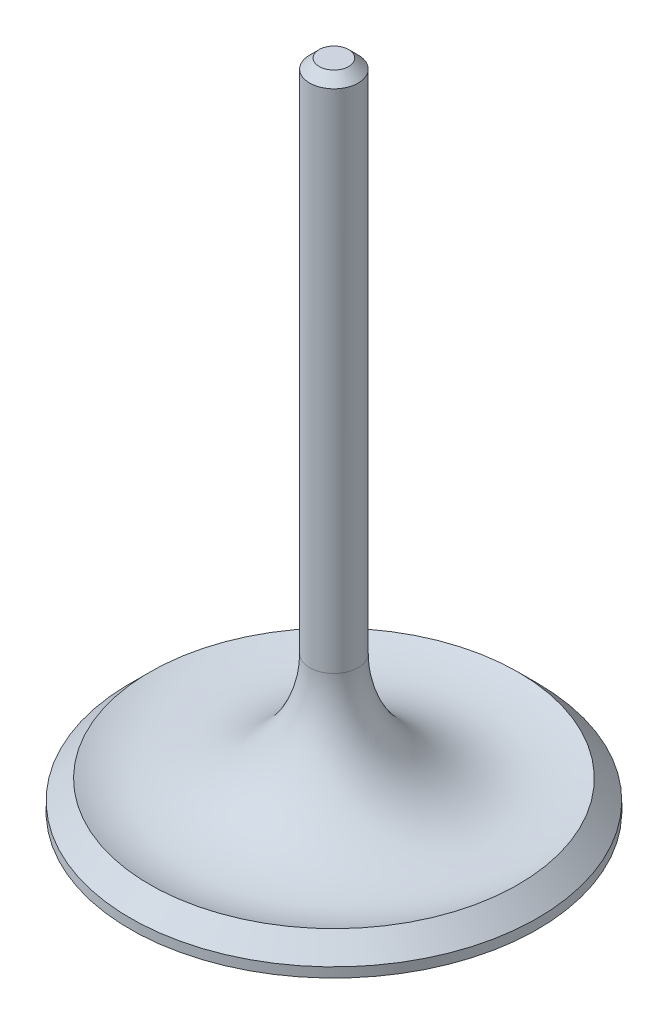
SolidWorks part; units mm, degrees
ref_plane "Front Plane" through (0, 0, 0) normal (0, 0, 1) x (1, 0, 0)
ref_plane "Top Plane" through (0, 0, 0) normal (0, 1, 0) x (1, 0, 0)
ref_plane "Right Plane" through (0, 0, 0) normal (1, 0, 0) x (0, 0, -1)
sketch "Sketch1" plane through (0, 0, 0) normal (1, 0, 0) x (0, 0, -1)
  line L0 (0, 0) -> (0, 85.55)
  line L1 (0, 85.55) -> (3.18, 85.55)
  line L2 (3.18, 85.55) -> (3.18, 17.9547)
  line L3 (24.13, 3.81) -> (26.67, 1.27)
  line L4 (26.67, 1.27) -> (26.67, 0)
  line L5 (26.67, 0) -> (0, 0)
  arc A0 (3.18, 17.9547) -> (24.13, 3.81) centre (18.43, 17.9547) ccw
  dimension "D4" = 15.25
  dimension "D1" = 85.55
  dimension "D2" = 26.67
  dimension "D3" = 3.18
  dimension "D5" = 3.81
  dimension "D6" = 1.27
  dimension "D7" = 45
revolve "Revolve1" add sketch "Sketch1" angle 360 about L0
chamfer "Chamfer1" distance 1.25 angle 45 1 edges at (0, 85.55, -3.18)
